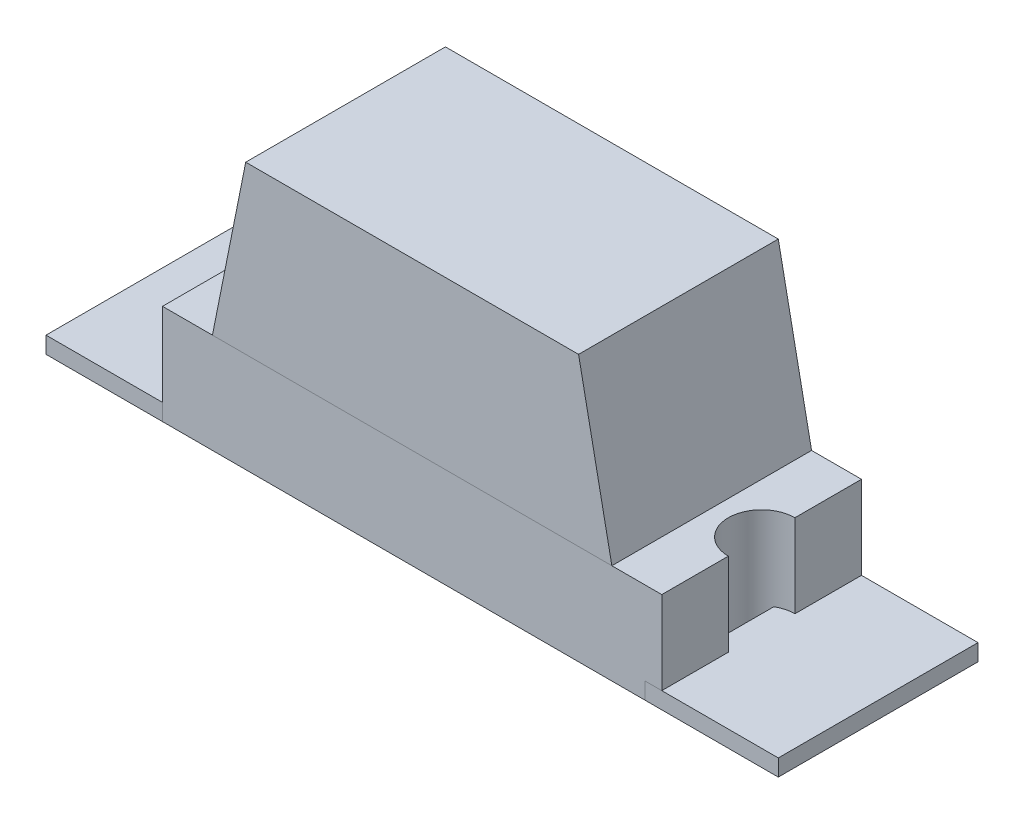
SolidWorks part; units mm, degrees
material "E-Glass Fiber"
ref_plane "Front Plane" through (0, 0, 0) normal (0, 0, 1) x (1, 0, 0)
ref_plane "Top Plane" through (0, 0, 0) normal (0, 1, 0) x (1, 0, 0)
ref_plane "Right Plane" through (0, 0, 0) normal (1, 0, 0) x (0, 0, -1)
sketch "Sketch1" plane through (0, 0, 0) normal (0, 1, 0) x (1, 0, 0)
  line L0 (-0.44, 0) -> (0.44, 0) construction
  line L1 (-0.75, 0.3) -> (0.75, 0.3)
  line L2 (-0.75, 0.3) -> (-0.75, 0.1)
  line L3 (-0.75, -0.3) -> (0.75, -0.3)
  line L4 (0.75, 0.3) -> (0.75, 0.1)
  line L5 (0, -0.385) -> (0, 0.385) construction
  line L6 (0.75, -0.1) -> (0.75, -0.3)
  line L7 (-0.75, -0.1) -> (-0.75, -0.3)
  arc A0 (-0.75, -0.1) -> (-0.75, 0.1) centre (-0.75, 0) ccw
  arc A1 (0.75, 0.1) -> (0.75, -0.1) centre (0.75, 0) ccw
  dimension "D5" = 0.2
  dimension "D1" = 0.6
  dimension "D2" = 0.3
  dimension "D3" = 1.5
  dimension "D4" = 0.75
extrude "Boss-Extrude1" add sketch "Sketch1" along normal blind 0.3
sketch "Sketch3" plane through (0, 0, 0) normal (0, 0, 1) x (1, 0, 0)
  line L0 (0, 0.8092) -> (0, -0.2421) construction
  line L1 (-0.75, 0.3) -> (0.75, 0.3) construction
  line L2 (0, 0.5) -> (0.25, 0.5)
  line L3 (0, 0.5) -> (0, 0.3)
  line L4 (0, 0.3) -> (0.25, 0.3)
  line L5 (0.25, 0.5) -> (0.25, 0.3)
  dimension "D1" = 0.5
  dimension "D2" = 0.2
revolve "Revolve1" add sketch "Sketch3" angle 360 about L0
sketch "Sketch4" plane through (0, 0, 0) normal (0, 1, 0) x (1, 0, 0)
  line L0 (0, 0.3) -> (0, -0.3) construction
  line L1 (0, -0.385) -> (0, 0.385) construction
  line L2 (0.75, 0.3) -> (-0.75, 0.3) construction
  line L3 (-0.75, -0.3) -> (0.75, -0.3) construction
  line L4 (0.7, 0.3) -> (0.7, -0.3)
  line L5 (1.1, -0.3) -> (0.7, -0.3)
  line L6 (-1.1, 0.3) -> (-0.7, 0.3)
  line L7 (-1.1, 0.3) -> (-1.1, -0.3)
  line L8 (-1.1, -0.3) -> (-0.7, -0.3)
  line L9 (-0.7, 0.3) -> (-0.7, -0.3)
  line L10 (1.1, 0.3) -> (1.1, -0.3)
  line L11 (1.1, 0.3) -> (0.7, 0.3)
  line L12 (-0.44, 0) -> (0.44, 0) construction
  dimension "D1" = 0.7
  dimension "D2" = 0.4
  dimension "D5" = 0.3
  dimension "D6" = 0.6
extrude "Boss-Extrude4" add sketch "Sketch4" along normal blind 0.05 separate body
sketch "Sketch2" plane through (0, 0, 0) normal (0, 0, 1) x (1, 0, 0)
  line L0 (-0.6, 0.3) -> (0.6, 0.3)
  line L1 (-0.75, 0.3) -> (0.75, 0.3) construction
  line L2 (0.6, 0.3) -> (0.5, 0.8)
  line L3 (0.5, 0.8) -> (-0.5, 0.8)
  line L4 (-0.5, 0.8) -> (-0.6, 0.3)
  line L5 (0, -0.385) -> (0, 0.385) construction
  line L6 (0, 0.8) -> (0, 0.3) construction
  dimension "D1" = 1
  dimension "D2" = 0.5
  dimension "D3" = 1.2
  dimension "D4" = 0.6
extrude "Boss-Extrude5" add sketch "Sketch2" along normal mid plane 0.6 separate body
